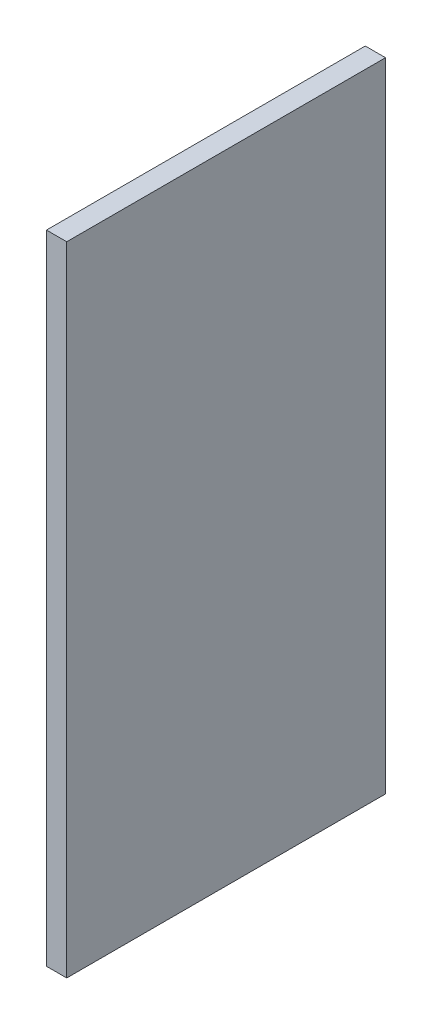
SolidWorks part; units mm, degrees
material "Oak"
ref_plane "Front Plane" through (0, 0, 0) normal (0, 0, 1) x (1, 0, 0)
ref_plane "Top Plane" through (0, 0, 0) normal (0, 1, 0) x (1, 0, 0)
ref_plane "Right Plane" through (0, 0, 0) normal (1, 0, 0) x (0, 0, -1)
sketch "Sketch1" plane through (0, 0, 0) normal (1, 0, 0) x (0, 0, -1)
  line L1 (0, 0) -> (100, 0)
  line L2 (0, 0) -> (0, -200)
  line L3 (0, -200) -> (100, -200)
  line L4 (100, 0) -> (100, -200)
  dimension "D1" = 100
  dimension "D2" = 200
extrude "Boss-Extrude1" add sketch "Sketch1" along normal blind 6.35
